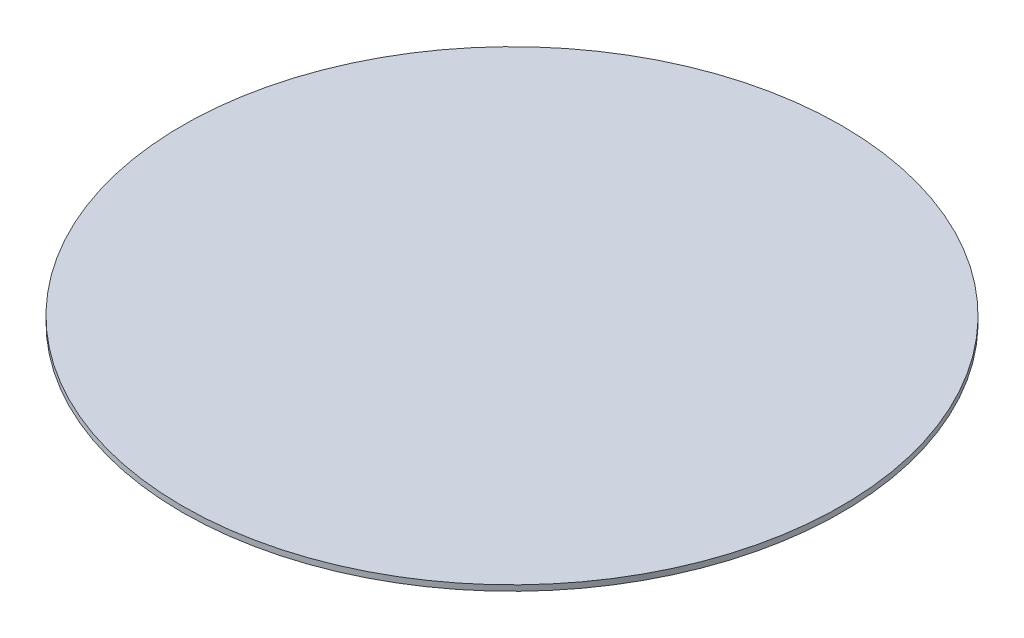
SolidWorks part; units mm, degrees
ref_plane "Front" through (0, 0, 0) normal (0, 0, 1) x (1, 0, 0)
ref_plane "Top" through (0, 0, 0) normal (0, 1, 0) x (1, 0, 0)
ref_plane "Right" through (0, 0, 0) normal (1, 0, 0) x (0, 0, -1)
sketch "Sketch1" plane through (0, 0, 0) normal (0, 1, 0) x (1, 0, 0)
  circle A0 centre (0, 0) radius 161.5
  dimension "D1" = 323
extrude "Boss-Extrude1" add sketch "Sketch1" along normal blind 2.75
